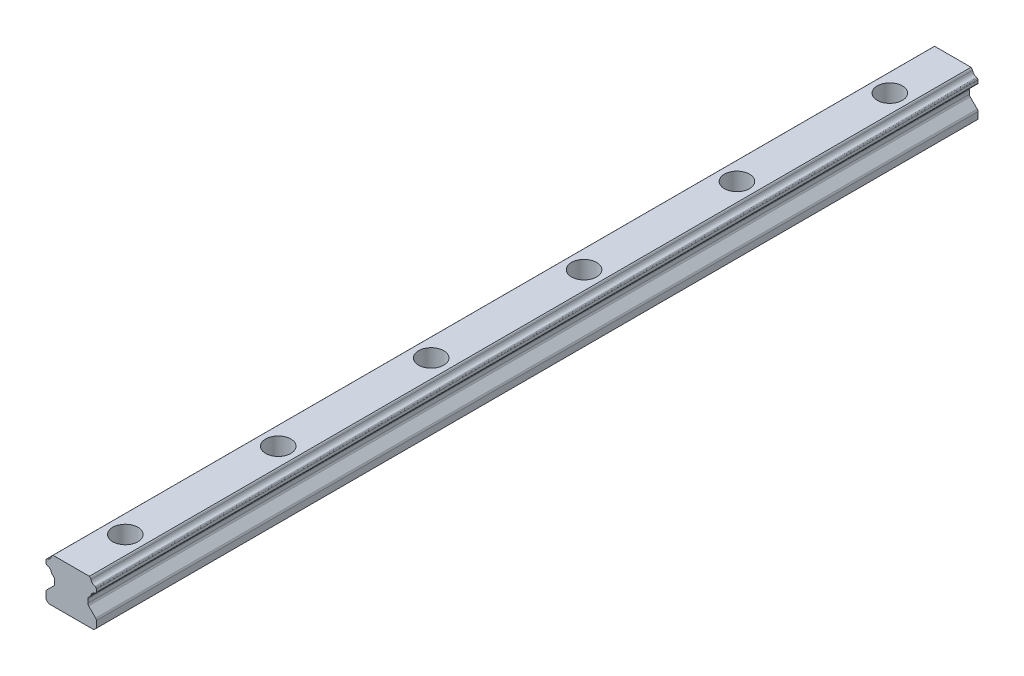
SolidWorks part; units mm, degrees
material "Plain Carbon Steel"
ref_plane "Front Plane" through (0, 0, 0) normal (0, 0, 1) x (1, 0, 0)
ref_plane "Top Plane" through (0, 0, 0) normal (0, 1, 0) x (1, 0, 0)
ref_plane "Right Plane" through (0, 0, 0) normal (1, 0, 0) x (0, 0, -1)
sketch3d "3DSketch1"
  line L0 (0, 0, 0) -> (0, 0, 350)
  dimension "D1" = 350
other "Hgr HGR20(1)"
ref_plane "Plane1" through (0, 0, 0) normal (0, 0, 1) x (1, 0, 0)
sketch "Sketch12" plane through (0, 0, 0) normal (0, 0, 1) x (1, 0, 0)
  line L0 (-9, 0) -> (9, 0)
  line L1 (9, 0) -> (10, 1)
  line L2 (10, 1) -> (10, 3.6565)
  line L3 (9.7071, 4.3636) -> (6.8929, 7.1778)
  line L4 (6.6, 7.8849) -> (6.6, 9.4451)
  line L5 (6.8929, 10.1522) -> (7.6302, 10.8894)
  line L6 (9.6906, 12.9499) -> (9.8536, 13.1128)
  line L7 (10, 13.4664) -> (10, 14.5236)
  line L8 (9.8536, 14.8772) -> (9.6785, 15.0522)
  line L9 (7.6325, 17.0982) -> (7.2307, 17.5)
  line L10 (7.2307, 17.5) -> (-7.2307, 17.5)
  line L11 (-7.2307, 17.5) -> (-7.6325, 17.0982)
  line L12 (-9.6785, 15.0522) -> (-9.8536, 14.8772)
  line L13 (-10, 14.5236) -> (-10, 13.4664)
  line L14 (-9.8536, 13.1128) -> (-9.6906, 12.9499)
  line L15 (-7.6302, 10.8894) -> (-6.8929, 10.1522)
  line L16 (-6.6, 9.4451) -> (-6.6, 7.8849)
  line L17 (-6.8929, 7.1778) -> (-9.7071, 4.3636)
  line L18 (-10, 3.6565) -> (-10, 1)
  line L19 (-10, 1) -> (-9, 0)
  arc A0 (10, 3.6565) -> (9.7071, 4.3636) centre (9, 3.6565) ccw
  arc A1 (6.6, 7.8849) -> (6.8929, 7.1778) centre (7.6, 7.8849) ccw
  arc A2 (6.8929, 10.1522) -> (6.6, 9.4451) centre (7.6, 9.4451) ccw
  arc A3 (7.6302, 10.8894) -> (7.8468, 11.2275) centre (7.3529, 11.3055) ccw
  arc A4 (9.4318, 12.8125) -> (7.8468, 11.2275) centre (9.8106, 10.8487) ccw
  arc A5 (9.4318, 12.8125) -> (9.6906, 12.9499) centre (9.3371, 13.3035) ccw
  arc A6 (9.8536, 13.1128) -> (10, 13.4664) centre (9.5, 13.4664) ccw
  arc A7 (10, 14.5236) -> (9.8536, 14.8772) centre (9.5, 14.5236) ccw
  arc A8 (9.6785, 15.0522) -> (9.422, 15.1892) centre (9.3249, 14.6987) ccw
  arc A9 (7.8482, 16.763) -> (9.422, 15.1892) centre (9.8101, 17.1511) ccw
  arc A10 (7.8482, 16.763) -> (7.6325, 17.0982) centre (7.3547, 16.6825) ccw
  arc A11 (-7.6325, 17.0982) -> (-7.8482, 16.763) centre (-7.3547, 16.6825) ccw
  arc A12 (-9.422, 15.1892) -> (-7.8482, 16.763) centre (-9.8101, 17.1511) ccw
  arc A13 (-9.422, 15.1892) -> (-9.6785, 15.0522) centre (-9.3249, 14.6987) ccw
  arc A14 (-9.8536, 14.8772) -> (-10, 14.5236) centre (-9.5, 14.5236) ccw
  arc A15 (-10, 13.4664) -> (-9.8536, 13.1128) centre (-9.5, 13.4664) ccw
  arc A16 (-9.6906, 12.9499) -> (-9.4318, 12.8125) centre (-9.3371, 13.3035) ccw
  arc A17 (-7.8468, 11.2275) -> (-9.4318, 12.8125) centre (-9.8106, 10.8487) ccw
  arc A18 (-7.8468, 11.2275) -> (-7.6302, 10.8894) centre (-7.3529, 11.3055) ccw
  arc A19 (-6.6, 9.4451) -> (-6.8929, 10.1522) centre (-7.6, 9.4451) ccw
  arc A20 (-6.8929, 7.1778) -> (-6.6, 7.8849) centre (-7.6, 7.8849) ccw
  arc A21 (-9.7071, 4.3636) -> (-10, 3.6565) centre (-9, 3.6565) ccw
  point P64 (0, 0)
hole_wizard "CBORE for M5 Hex Socket Head Cap Screw1" positions "Sketch13" profile "Sketch15" counterbore size "M5" standard "DIN" end condition up to next
sketch "Sketch13" plane through (0, 17.5, 0) normal (0, 1, 0) x (1, 0, 0)
  line L0 (7.2307, 0) -> (-7.2307, 0) construction
  point P0 (0, -25)
  dimension "D1" = 25
sketch "Sketch15" plane through (0, 17.5, 25) normal (1, 0, 0) x (0, 0, 1)
  line L0 (0, 0) -> (0, 17.5)
  line L1 (0, 17.5) -> (2.9, 17.5)
  line L3 (2.9, 17.5) -> (2.9, 8.5)
  line L4 (2.9, 8.5) -> (5, 8.5)
  line L5 (5, 8.5) -> (5, 0)
  line L7 (5, 0) -> (0, 0)
  line L11 (0, -6.35) -> (0, 107.95) construction
  dimension "Thru Hole Dia." = 5.8
  dimension "Thru Hole Depth" = 17.5
  dimension "C'Bore Dia." = 10
  dimension "C'Bore Depth" = 8.5
pattern_linear "LPattern1" count 6 spacing 60.7 along (0, 0, 1) of "CBORE for M5 Hex Socket Head Cap Screw1"
